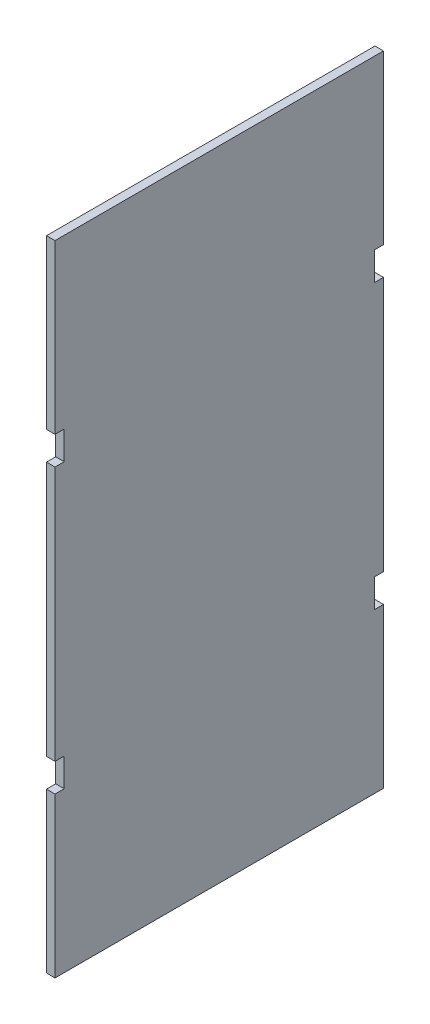
SolidWorks part; units mm, degrees
ref_plane "Front Plane" through (0, 0, 0) normal (0, 0, 1) x (1, 0, 0)
ref_plane "Top Plane" through (0, 0, 0) normal (0, 1, 0) x (1, 0, 0)
ref_plane "Right Plane" through (0, 0, 0) normal (1, 0, 0) x (0, 0, -1)
sketch "Sketch1" plane through (0, 0, 0) normal (1, 0, 0) x (0, 0, -1)
  line L0 (0, 0) -> (232, 0)
  line L2 (232, 451) -> (0, 451)
  line L5 (0, 312.5) -> (6.5, 312.5)
  line L6 (6.5, 312.5) -> (6.5, 332.5)
  line L7 (6.5, 332.5) -> (0, 332.5)
  line L8 (232, 332.5) -> (225.5, 332.5)
  line L10 (225.5, 332.5) -> (225.5, 312.5)
  line L11 (225.5, 312.5) -> (232, 312.5)
  line L12 (232, 132.5) -> (225.5, 132.5)
  line L14 (225.5, 132.5) -> (225.5, 112.5)
  line L15 (225.5, 112.5) -> (232, 112.5)
  line L16 (6.5, 132.5) -> (0, 132.5)
  line L17 (6.5, 112.5) -> (6.5, 132.5)
  line L19 (0, 112.5) -> (6.5, 112.5)
  line L20 (0, 451) -> (0, 332.5)
  line L21 (0, 312.5) -> (0, 132.5)
  line L22 (0, 112.5) -> (0, 0)
  line L23 (232, 0) -> (232, 112.5)
  line L24 (232, 132.5) -> (232, 312.5)
  line L25 (232, 332.5) -> (232, 451)
  line L27 (232, 312.5) -> (232, 332.5) [skipped]
  line L28 (232, 112.5) -> (232, 132.5) [skipped]
  dimension "D1" = 451
  dimension "D2" = 232
  dimension "D3" = 6.5
  dimension "D4" = 20
  dimension "D5" = 118.5
  dimension "D10" = 200
  dimension "D7" = 2
  dimension "D8" = 2
extrude "Boss-Extrude1" add sketch "Sketch1" along normal blind 6
